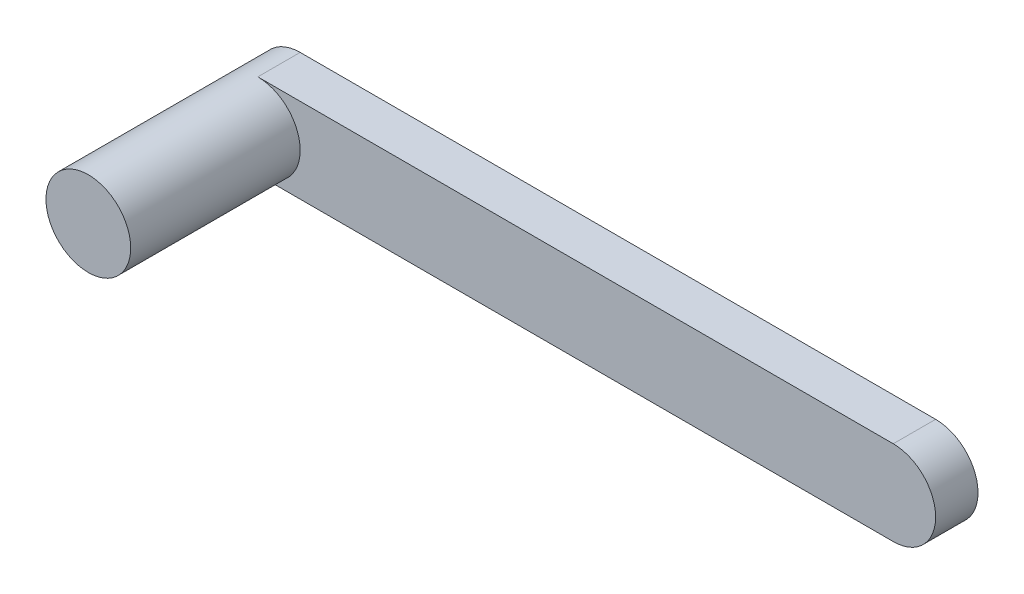
SolidWorks part; units mm, degrees
ref_plane "Front Plane" through (0, 0, 0) normal (0, 0, 1) x (1, 0, 0)
ref_plane "Top Plane" through (0, 0, 0) normal (0, 1, 0) x (1, 0, 0)
ref_plane "Right Plane" through (0, 0, 0) normal (1, 0, 0) x (0, 0, -1)
sketch "Sketch1" plane through (0, 0, 0) normal (0, 0, 1) x (1, 0, 0)
  line L0 (0, -2) -> (30, -2)
  line L1 (0, 2) -> (30, 2)
  arc A0 (0, 2) -> (0, -2) centre (0, 0) ccw
  arc A1 (30, -2) -> (30, 2) centre (30, 0) ccw
  dimension "D2" = 4
  dimension "D3" = 4
  dimension "D1" = 30
extrude "Boss-Extrude1" add sketch "Sketch1" along normal blind 2
sketch "Sketch2" plane through (0, 0, 2) normal (0, 0, 1) x (1, 0, 0)
  circle A0 centre (0, 0) radius 2
  dimension "D1" = 4
extrude "Boss-Extrude2" add sketch "Sketch2" along normal blind 8
